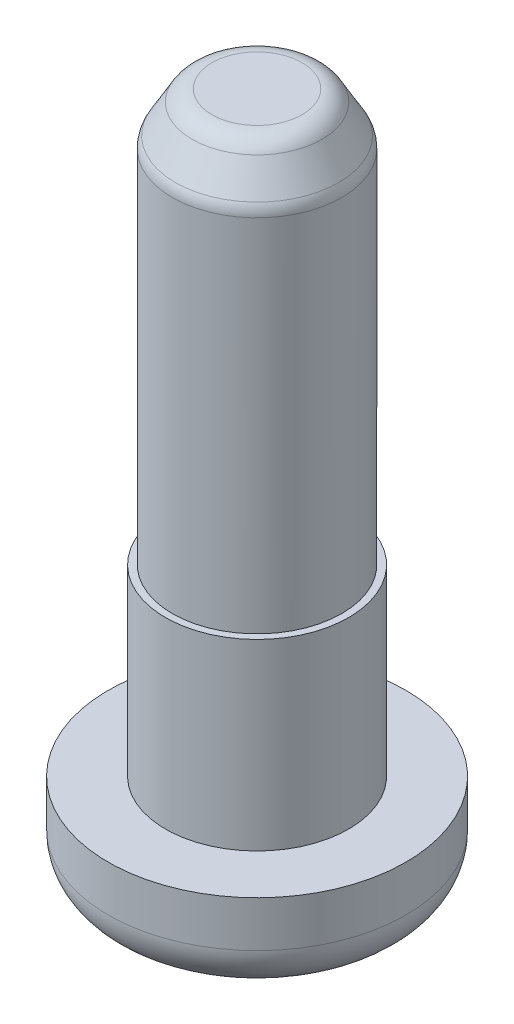
SolidWorks part; units mm, degrees
material "ABS"
ref_plane "Front" through (0, 0, 0) normal (0, 0, 1) x (1, 0, 0)
ref_plane "Top" through (0, 0, 0) normal (0, 1, 0) x (1, 0, 0)
ref_plane "Right" through (0, 0, 0) normal (1, 0, 0) x (0, 0, -1)
sketch "Sketch1" plane through (0, 0, 0) normal (0, 1, 0) x (1, 0, 0)
  circle A0 centre (0, 0) radius 4
  dimension "D1" = 8
extrude "Boss-Extrude1" add sketch "Sketch1" along normal blind 26
sketch "Sketch2" plane through (0, 0, 0) normal (0, -1, 0) x (1, 0, 0)
  circle A0 centre (0, 0) radius 6.5
  dimension "D1" = 13
extrude "Boss-Extrude2" add sketch "Sketch2" along normal blind 4
sketch "Sketch3" plane through (0, 26, 0) normal (0, 1, 0) x (1, 0, 0)
  circle A0 centre (0, 0) radius 3.7
  circle A1 centre (0, 0) radius 4
  circle A2 centre (0, 0) radius 4 construction
  dimension "D1" = 0.3
extrude "Cut-Extrude1" cut sketch "Sketch3" against normal offset from surface (18 mm away) 8 up to face at (0, 0, 4)
fillet "Fillet2" radius 2 1 edges at (0, -4, -6.5)
chamfer "Chamfer1" distance 2 angle 30 1 edges at (0, 26, 3.7)
fillet "Fillet3" radius 1 2 edges at (0, 24, 3.7) (0, 26, 2.5453)
